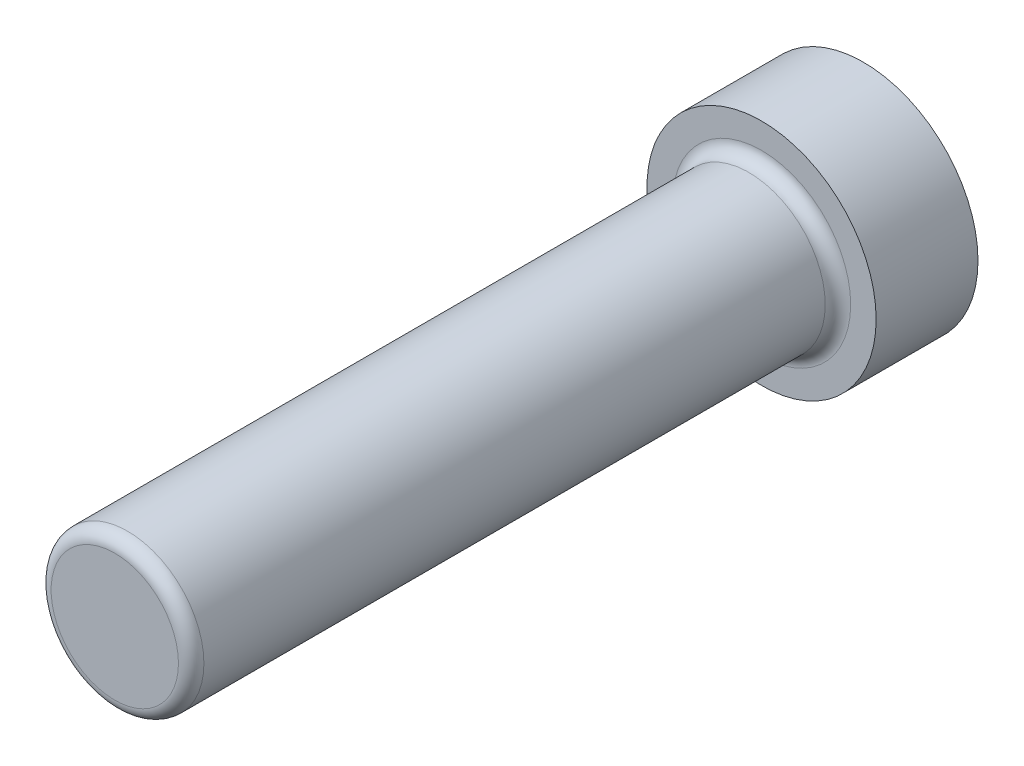
SolidWorks part; units mm, degrees
ref_plane "Front Plane" through (0, 0, 0) normal (0, 0, 1) x (1, 0, 0)
ref_plane "Top Plane" through (0, 0, 0) normal (0, 1, 0) x (1, 0, 0)
ref_plane "Right Plane" through (0, 0, 0) normal (1, 0, 0) x (0, 0, -1)
sketch "Sketch1" plane through (0, 0, 0) normal (0, 0, 1) x (1, 0, 0)
  circle A0 centre (0, 0) radius 1.5
  dimension "D1" = 3
extrude "Boss-Extrude1" add sketch "Sketch1" along normal blind 12.7 contours A0
sketch "Sketch3" plane through (0, 0, 0) normal (0, 0, 1) x (1, 0, 0)
  circle A0 centre (0, 0) radius 2.25
  dimension "D1" = 4.5
extrude "Boss-Extrude2" add sketch "Sketch3" against normal blind 2
fillet "Fillet2" radius 0.25 1 edges at (1.5, 0, 12.7)
fillet "Fillet3" radius 0.25 1 edges at (1.5, 0, 0)
